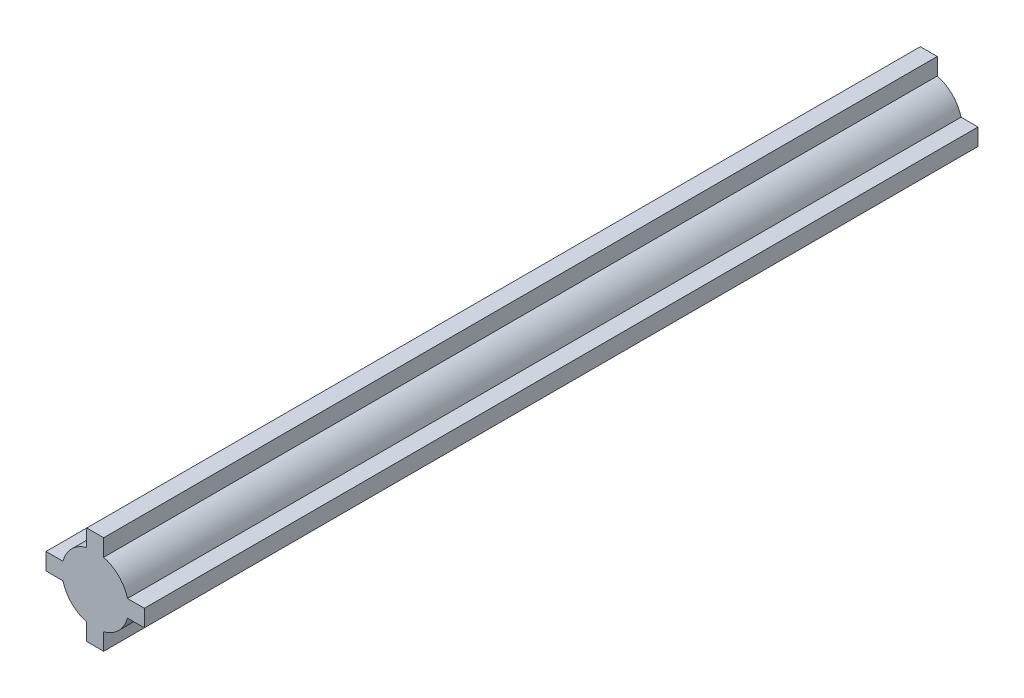
SolidWorks part; units mm, degrees
material "AISI 1020"
ref_plane "Front Plane" through (0, 0, 0) normal (0, 0, 1) x (1, 0, 0)
ref_plane "Top Plane" through (0, 0, 0) normal (0, 1, 0) x (1, 0, 0)
ref_plane "Right Plane" through (0, 0, 0) normal (1, 0, 0) x (0, 0, -1)
sketch "Sketch1" plane through (0, 0, 0) normal (0, 0, 1) x (1, 0, 0)
  line L0 (-0.254, 0.9672) -> (0.254, 0.9672)
  line L1 (-0.254, 0.9672) -> (-0.254, 1.4752)
  line L2 (0.254, 0.9672) -> (0.254, 1.4752)
  line L3 (-0.254, 1.4752) -> (0.254, 1.4752)
  line L4 (-0.254, -0.9672) -> (0.254, -0.9672)
  line L5 (-0.254, -0.9672) -> (-0.254, -1.4752)
  line L6 (0.254, -0.9672) -> (0.254, -1.4752)
  line L7 (-0.254, -1.4752) -> (0.254, -1.4752)
  line L8 (0.9672, 0.254) -> (0.9672, -0.254)
  line L9 (0.9672, 0.254) -> (1.4752, 0.254)
  line L10 (0.9672, -0.254) -> (1.4752, -0.254)
  line L11 (1.4752, 0.254) -> (1.4752, -0.254)
  line L12 (-0.9672, 0.254) -> (-0.9672, -0.254)
  line L13 (-0.9672, 0.254) -> (-1.4752, 0.254)
  line L14 (-0.9672, -0.254) -> (-1.4752, -0.254)
  line L15 (-1.4752, 0.254) -> (-1.4752, -0.254)
  circle A0 centre (0, 0) radius 1
  dimension "D1" = 2
  dimension "D2" = 0.508
  dimension "D3" = 0.508
  dimension "D4" = 0.508
  dimension "D5" = 0.508
  dimension "D6" = 0.508
  dimension "D7" = 0.508
  dimension "D8" = 0.508
  dimension "D9" = 0.508
extrude "Boss-Extrude1" add sketch "Sketch1" along normal mid plane 25 contours L0 A0 | A0 L2 L3 L1 | L15 L14 L12 L13 | L7 L6 L4 L5 | L11 L10 L8 L9
